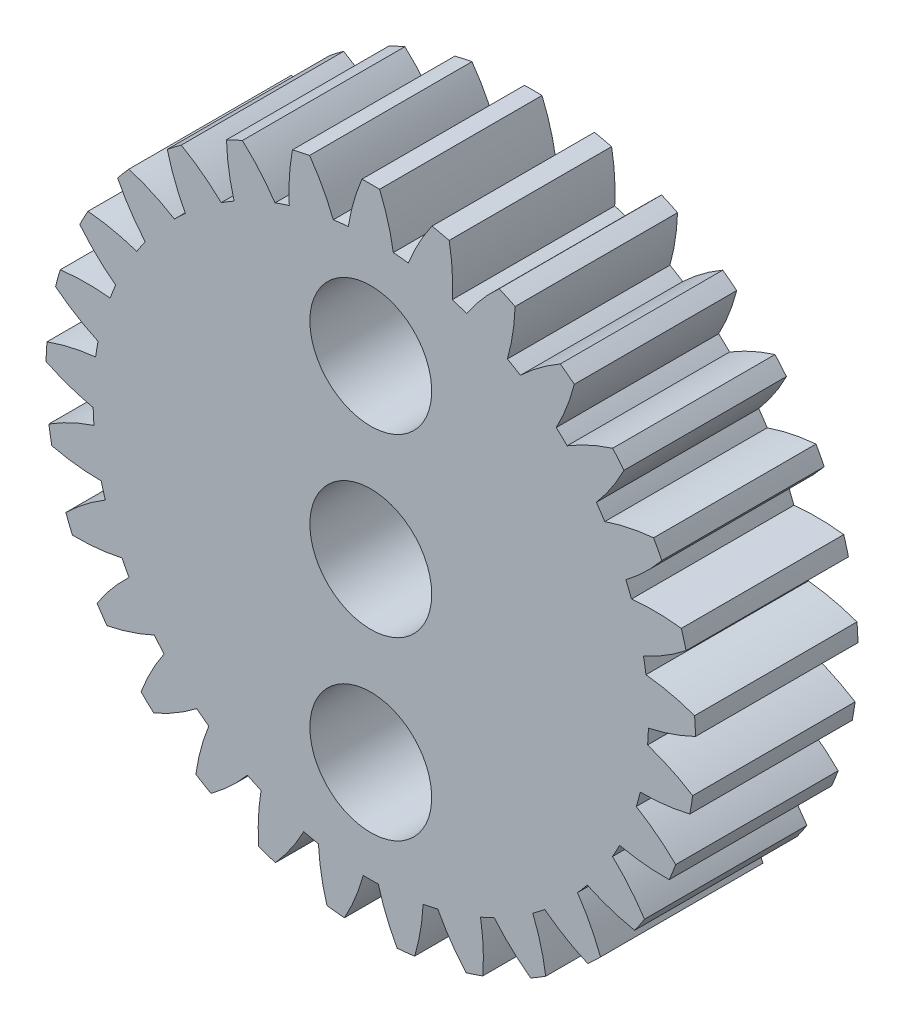
SolidWorks part; units mm, degrees
material "6061-T6 (SS)"
ref_plane "Alzado" through (0, 0, 0) normal (0, 0, 1) x (1, 0, 0)
ref_plane "Planta" through (0, 0, 0) normal (0, 1, 0) x (1, 0, 0)
ref_plane "Vista lateral" through (0, 0, 0) normal (1, 0, 0) x (0, 0, -1)
sketch "Croquis1" plane through (0, 0, 0) normal (0, 0, 1) x (1, 0, 0)
  arc A0 (-2.8959, 11.6449) -> (-3.011, 9.8062) centre (4.6106, 10.2524) ccw
  arc A1 (-3.011, 9.8062) -> (-3.5374, 9.6288) centre (0, 0) ccw
  arc A2 (-3.5374, 9.6288) -> (-4.7417, 11.0229) centre (-9.8749, 5.3716) ccw
  arc A3 (-4.7417, 11.0229) -> (-5.3315, 10.7501) centre (0, 0) ccw
  arc A4 (-5.3315, 10.7501) -> (-5.0486, 8.9296) centre (2.2988, 11.0038) ccw
  arc A5 (-5.0486, 8.9296) -> (-5.5246, 8.6432) centre (0, 0) ccw
  arc A6 (-5.5246, 8.6432) -> (-7.0005, 9.7459) centre (-10.7988, 3.1232) ccw
  arc A7 (-7.0005, 9.7459) -> (-7.5178, 9.3526) centre (0, 0) ccw
  arc A8 (-7.5178, 9.3526) -> (-6.8502, 7.6356) centre (-0.1204, 11.2407) ccw
  arc A9 (-6.8502, 7.6356) -> (-7.2535, 7.2535) centre (0, 0) ccw
  arc A10 (-7.2535, 7.2535) -> (-8.9319, 8.0132) centre (-11.2177, 0.7288) ccw
  arc A11 (-8.9319, 8.0132) -> (-9.3526, 7.5178) centre (0, 0) ccw
  arc A12 (-9.3526, 7.5178) -> (-8.3314, 5.9845) centre (-2.534, 10.952) ccw
  arc A13 (-8.3314, 5.9845) -> (-8.6432, 5.5246) centre (0, 0) ccw
  arc A14 (-8.6432, 5.5246) -> (-10.4457, 5.9057) centre (-11.1121, -1.6997) ccw
  arc A15 (-10.4457, 5.9057) -> (-10.7501, 5.3315) centre (0, 0) ccw
  arc A16 (-10.7501, 5.3315) -> (-9.4231, 4.0535) centre (-4.8291, 10.1513) ccw
  arc A17 (-9.4231, 4.0535) -> (-9.6288, 3.5374) centre (0, 0) ccw
  arc A18 (-9.6288, 3.5374) -> (-11.471, 3.5221) centre (-10.4869, -4.0488) ccw
  arc A19 (-11.471, 3.5221) -> (-11.6449, 2.8959) centre (0, 0) ccw
  arc A20 (-11.6449, 2.8959) -> (-10.0742, 1.9331) centre (-6.8985, 8.8758) ccw
  arc A21 (-10.0742, 1.9331) -> (-10.1641, 1.3848) centre (0, 0) ccw
  arc A22 (-10.1641, 1.3848) -> (-11.96, 0.9739) centre (-9.3714, -6.2085) ccw
  arc A23 (-11.96, 0.9739) -> (-11.9952, 0.3249) centre (0, 0) ccw
  arc A24 (-11.9952, 0.3249) -> (-10.2543, -0.2778) centre (-8.6452, 7.1853) ccw
  arc A25 (-10.2543, -0.2778) -> (-10.2242, -0.8325) centre (0, 0) ccw
  arc A26 (-10.2242, -0.8325) -> (-11.8897, -1.6199) centre (-7.8177, -8.0779) ccw
  arc A27 (-11.8897, -1.6199) -> (-11.7846, -2.2613) centre (0, 0) ccw
  arc A28 (-11.7846, -2.2613) -> (-9.9548, -2.4756) centre (-9.9877, 5.1589) ccw
  arc A29 (-9.9548, -2.4756) -> (-9.8062, -3.011) centre (0, 0) ccw
  arc A30 (-9.8062, -3.011) -> (-11.2635, -4.138) centre (-5.8984, -9.5696) ccw
  arc A31 (-11.2635, -4.138) -> (-11.0229, -4.7417) centre (0, 0) ccw
  arc A32 (-11.0229, -4.7417) -> (-9.1899, -4.5578) centre (-10.8632, 2.8912) ccw
  arc A33 (-9.1899, -4.5578) -> (-8.9296, -5.0486) centre (0, 0) ccw
  arc A34 (-8.9296, -5.0486) -> (-10.1106, -6.4626) centre (-3.7033, -10.6139) ccw
  arc A35 (-10.1106, -6.4626) -> (-9.7459, -7.0005) centre (0, 0) ccw
  arc A36 (-9.7459, -7.0005) -> (-7.9952, -6.4268) centre (-11.2308, 0.4883) ccw
  arc A37 (-7.9952, -6.4268) -> (-7.6356, -6.8502) centre (0, 0) ccw
  arc A38 (-7.6356, -6.8502) -> (-8.485, -8.485) centre (-1.335, -11.1618) ccw
  arc A39 (-8.485, -8.485) -> (-8.0132, -8.9319) centre (0, 0) ccw
  arc A40 (-8.0132, -8.9319) -> (-6.4268, -7.9952) centre (-11.0732, -1.9374) ccw
  arc A41 (-6.4268, -7.9952) -> (-5.9845, -8.3314) centre (0, 0) ccw
  arc A42 (-5.9845, -8.3314) -> (-6.4626, -10.1106) centre (1.0956, -11.1879) ccw
  arc A43 (-6.4626, -10.1106) -> (-5.9057, -10.4457) centre (0, 0) ccw
  arc A44 (-5.9057, -10.4457) -> (-4.5578, -9.1899) centre (-10.3978, -4.2725) ccw
  arc A45 (-4.5578, -9.1899) -> (-4.0535, -9.4231) centre (0, 0) ccw
  arc A46 (-4.0535, -9.4231) -> (-4.138, -11.2635) centre (3.4751, -10.6908) ccw
  arc A47 (-4.138, -11.2635) -> (-3.5221, -11.471) centre (0, 0) ccw
  arc A48 (-3.5221, -11.471) -> (-2.4756, -9.9548) centre (-9.2363, -6.4078) ccw
  arc A49 (-2.4756, -9.9548) -> (-1.9331, -10.0742) centre (0, 0) ccw
  arc A50 (-1.9331, -10.0742) -> (-1.6199, -11.8897) centre (5.692, -9.6938) ccw
  arc A51 (-1.6199, -11.8897) -> (-0.9739, -11.96) centre (0, 0) ccw
  arc A52 (-0.9739, -11.96) -> (-0.2778, -10.2543) centre (-7.6428, -8.2435) ccw
  arc A53 (-0.2778, -10.2543) -> (0.2778, -10.2543) centre (0, 0) ccw
  arc A54 (0.2778, -10.2543) -> (0.9739, -11.96) centre (7.6428, -8.2435) ccw
  arc A55 (0.9739, -11.96) -> (1.6199, -11.8897) centre (0, 0) ccw
  arc A56 (1.6199, -11.8897) -> (1.9331, -10.0742) centre (-5.692, -9.6938) ccw
  arc A57 (1.9331, -10.0742) -> (2.4756, -9.9548) centre (0, 0) ccw
  arc A58 (2.4756, -9.9548) -> (3.5221, -11.471) centre (9.2363, -6.4078) ccw
  arc A59 (3.5221, -11.471) -> (4.138, -11.2635) centre (0, 0) ccw
  arc A60 (4.138, -11.2635) -> (4.0535, -9.4231) centre (-3.4751, -10.6908) ccw
  arc A61 (4.0535, -9.4231) -> (4.5578, -9.1899) centre (0, 0) ccw
  arc A62 (4.5578, -9.1899) -> (5.9057, -10.4457) centre (10.3978, -4.2725) ccw
  arc A63 (5.9057, -10.4457) -> (6.4626, -10.1106) centre (0, 0) ccw
  arc A64 (6.4626, -10.1106) -> (5.9845, -8.3314) centre (-1.0956, -11.1879) ccw
  arc A65 (5.9845, -8.3314) -> (6.4268, -7.9952) centre (0, 0) ccw
  arc A66 (6.4268, -7.9952) -> (8.0132, -8.9319) centre (11.0732, -1.9374) ccw
  arc A67 (8.0132, -8.9319) -> (8.485, -8.485) centre (0, 0) ccw
  arc A68 (8.485, -8.485) -> (7.6356, -6.8502) centre (1.335, -11.1618) ccw
  arc A69 (7.6356, -6.8502) -> (7.9952, -6.4268) centre (0, 0) ccw
  arc A70 (7.9952, -6.4268) -> (9.7459, -7.0005) centre (11.2308, 0.4883) ccw
  arc A71 (9.7459, -7.0005) -> (10.1106, -6.4626) centre (0, 0) ccw
  arc A72 (10.1106, -6.4626) -> (8.9296, -5.0486) centre (3.7033, -10.6139) ccw
  arc A73 (8.9296, -5.0486) -> (9.1899, -4.5578) centre (0, 0) ccw
  arc A74 (9.1899, -4.5578) -> (11.0229, -4.7417) centre (10.8632, 2.8912) ccw
  arc A75 (11.0229, -4.7417) -> (11.2635, -4.138) centre (0, 0) ccw
  arc A76 (11.2635, -4.138) -> (9.8062, -3.011) centre (5.8984, -9.5696) ccw
  arc A77 (9.8062, -3.011) -> (9.9548, -2.4756) centre (0, 0) ccw
  arc A78 (9.9548, -2.4756) -> (11.7846, -2.2613) centre (9.9877, 5.1589) ccw
  arc A79 (11.7846, -2.2613) -> (11.8897, -1.6199) centre (0, 0) ccw
  arc A80 (11.8897, -1.6199) -> (10.2242, -0.8325) centre (7.8177, -8.0779) ccw
  arc A81 (10.2242, -0.8325) -> (10.2543, -0.2778) centre (0, 0) ccw
  arc A82 (10.2543, -0.2778) -> (11.9952, 0.3249) centre (8.6452, 7.1853) ccw
  arc A83 (11.9952, 0.3249) -> (11.96, 0.9739) centre (0, 0) ccw
  arc A84 (11.96, 0.9739) -> (10.1641, 1.3848) centre (9.3714, -6.2085) ccw
  arc A85 (10.1641, 1.3848) -> (10.0742, 1.9331) centre (0, 0) ccw
  arc A86 (10.0742, 1.9331) -> (11.6449, 2.8959) centre (6.8985, 8.8758) ccw
  arc A87 (11.6449, 2.8959) -> (11.471, 3.5221) centre (0, 0) ccw
  arc A88 (11.471, 3.5221) -> (9.6288, 3.5374) centre (10.4869, -4.0488) ccw
  arc A89 (9.6288, 3.5374) -> (9.4231, 4.0535) centre (0, 0) ccw
  arc A90 (9.4231, 4.0535) -> (10.7501, 5.3315) centre (4.8291, 10.1513) ccw
  arc A91 (10.7501, 5.3315) -> (10.4457, 5.9057) centre (0, 0) ccw
  arc A92 (10.4457, 5.9057) -> (8.6432, 5.5246) centre (11.1121, -1.6997) ccw
  arc A93 (8.6432, 5.5246) -> (8.3314, 5.9845) centre (0, 0) ccw
  arc A94 (8.3314, 5.9845) -> (9.3526, 7.5178) centre (2.534, 10.952) ccw
  arc A95 (9.3526, 7.5178) -> (8.9319, 8.0132) centre (0, 0) ccw
  arc A96 (8.9319, 8.0132) -> (7.2535, 7.2535) centre (11.2177, 0.7288) ccw
  arc A97 (7.2535, 7.2535) -> (6.8502, 7.6356) centre (0, 0) ccw
  arc A98 (6.8502, 7.6356) -> (7.5178, 9.3526) centre (0.1204, 11.2407) ccw
  arc A99 (7.5178, 9.3526) -> (7.0005, 9.7459) centre (0, 0) ccw
  arc A100 (7.0005, 9.7459) -> (5.5246, 8.6432) centre (10.7988, 3.1232) ccw
  arc A101 (5.5246, 8.6432) -> (5.0486, 8.9296) centre (0, 0) ccw
  arc A102 (5.0486, 8.9296) -> (5.3315, 10.7501) centre (-2.2988, 11.0038) ccw
  arc A103 (5.3315, 10.7501) -> (4.7417, 11.0229) centre (0, 0) ccw
  arc A104 (4.7417, 11.0229) -> (3.5374, 9.6288) centre (9.8749, 5.3716) ccw
  arc A105 (3.5374, 9.6288) -> (3.011, 9.8062) centre (0, 0) ccw
  arc A106 (3.011, 9.8062) -> (2.8959, 11.6449) centre (-4.6106, 10.2524) ccw
  arc A107 (2.8959, 11.6449) -> (2.2613, 11.7846) centre (0, 0) ccw
  arc A108 (2.2613, 11.7846) -> (1.3848, 10.1641) centre (8.4893, 7.3689) ccw
  arc A109 (1.3848, 10.1641) -> (0.8325, 10.2242) centre (0, 0) ccw
  arc A110 (0.8325, 10.2242) -> (0.3249, 11.9952) centre (-6.7067, 9.0215) ccw
  arc A111 (0.3249, 11.9952) -> (-0.3249, 11.9952) centre (0, 0) ccw
  arc A112 (-0.3249, 11.9952) -> (-0.8325, 10.2242) centre (6.7067, 9.0215) ccw
  arc A113 (-0.8325, 10.2242) -> (-1.3848, 10.1641) centre (0, 0) ccw
  arc A114 (-1.3848, 10.1641) -> (-2.2613, 11.7846) centre (-8.4893, 7.3689) ccw
  arc A115 (-2.2613, 11.7846) -> (-2.8959, 11.6449) centre (0, 0) ccw
extrude "Saliente-Extruir1" add sketch "Croquis1" against normal mid plane 6
hole_wizard "Taladro de margen para M41" positions "Croquis3" profile "Croquis4" hole size "M4" standard "Ansi Metric" end condition up to next
sketch "Croquis3" plane through (0, 0, 3) normal (0, 0, 1) x (1, 0, 0)
  point P0 (0, 0)
sketch "Croquis4" plane through (0, 0, 3) normal (1, 0, 0) x (0, -1, 0)
  line L0 (0, 0) -> (0, 6)
  line L1 (0, 6) -> (2.25, 6)
  line L2 (2.25, 6) -> (2.25, 0)
  line L5 (2.25, 0) -> (0, 0)
  line L11 (0, -6.35) -> (0, 107.95) construction
  dimension "Diámetro de taladro hasta el siguiente" = 4.5
  dimension "Profundidad de taladro hasta el siguiente" = 6
sketch "Croquis5" plane through (0, 0, -3) normal (0, 0, -1) x (-1, 0, 0)
  line L0 (0, 0) -> (0, 6.5) construction
  line L3 (0, -6.5) -> (0, 0) construction
  circle A0 centre (0, 6.5) radius 2.25
  circle A1 centre (0, 6.5) radius 2.25 construction
  circle A2 centre (0, -6.5) radius 2.25
extrude "Cortar-Extruir1" cut sketch "Croquis5" against normal through all
